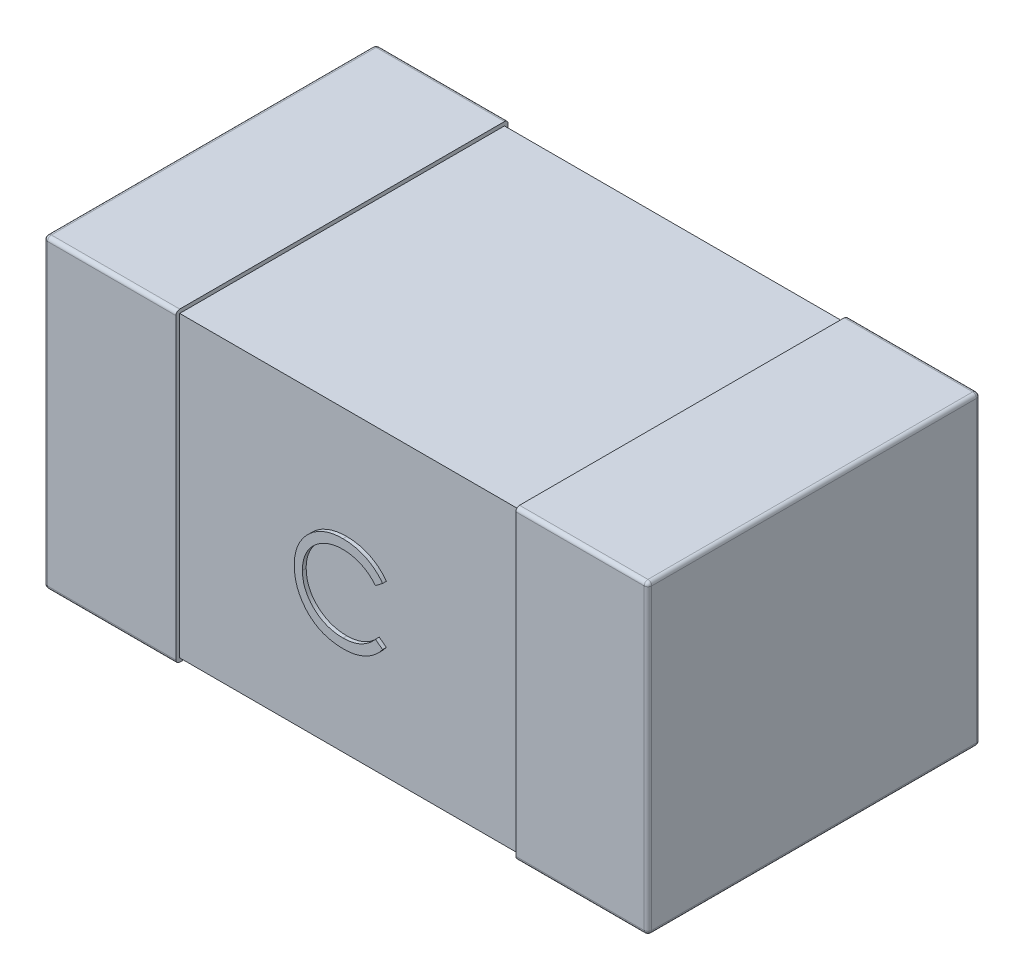
SolidWorks part; units mm, degrees
ref_plane "前视基准面" through (0, 0, 0) normal (0, 0, 1) x (1, 0, 0)
ref_plane "上视基准面" through (0, 0, 0) normal (0, 1, 0) x (1, 0, 0)
ref_plane "右视基准面" through (0, 0, 0) normal (1, 0, 0) x (0, 0, -1)
sketch "草图3" plane through (0, 0, 0) normal (0, 0, 1) x (1, 0, 0)
  line L0 (0, 0.9202) -> (0, -0.6542) construction
  line L1 (-0.8, 0.405) -> (-0.45, 0.405)
  line L2 (-0.8, 0.405) -> (-0.8, -0.405)
  line L3 (-0.8, -0.405) -> (-0.45, -0.405)
  line L4 (-0.45, 0.405) -> (-0.45, -0.405)
  line L5 (-0.8, 0.405) -> (-0.45, -0.405) construction
  line L6 (-0.8, -0.405) -> (-0.45, 0.405) construction
  line L7 (0.8, -0.405) -> (0.45, 0.405) construction
  line L8 (0.8, 0.405) -> (0.45, -0.405) construction
  line L9 (0.45, 0.405) -> (0.45, -0.405)
  line L10 (0.8, -0.405) -> (0.45, -0.405)
  line L11 (0.8, 0.405) -> (0.8, -0.405)
  line L12 (0.8, 0.405) -> (0.45, 0.405)
  point P0 (-0.625, 0)
  point P12 (0.625, 0)
  dimension "D1" = 0.35
  dimension "D2" = 0.81
  dimension "D3" = 0.8
extrude "凸台-拉伸1" add sketch "草图3" along normal blind 0.87 and the other way blind 0.01
sketch "草图5" plane through (0, 0, 0) normal (1, 0, 0) x (0, 0, -1)
  line L0 (0, 0.395) -> (0, -0.395)
  line L1 (0, -0.395) -> (-0.86, -0.395)
  line L2 (-0.86, -0.395) -> (-0.86, 0.395)
  line L3 (-0.86, 0.395) -> (0, 0.395)
  dimension "D1" = 0.79
  dimension "D2" = 0.86
extrude "凸台-拉伸3" add sketch "草图5" along normal mid plane 0.91
fillet "圆角3" radius 0.01 16 edges at (0.8, 0, -0.01) (0.8, -0.405, 0.43) (0.8, 0, 0.87) (0.8, 0.405, 0.43) (-0.8, 0, -0.01) (-0.8, 0.405, 0.43) (-0.8, 0, 0.87) (-0.8, -0.405, 0.43) (0.625, 0.405, -0.01) (0.625, -0.405, -0.01) (0.625, -0.405, 0.87) (0.625, 0.405, 0.87) (-0.625, -0.405, -0.01) (-0.625, -0.405, 0.87) (-0.625, 0.405, -0.01) (-0.625, 0.405, 0.87)
sketch "草图6" plane through (0, 0, 0.86) normal (0, 0, 1) x (1, 0, 0)
  text T0 "C" font "Century Gothic" height 0.24
extrude "凸台-拉伸4" add sketch "草图6" along normal blind 0.01
